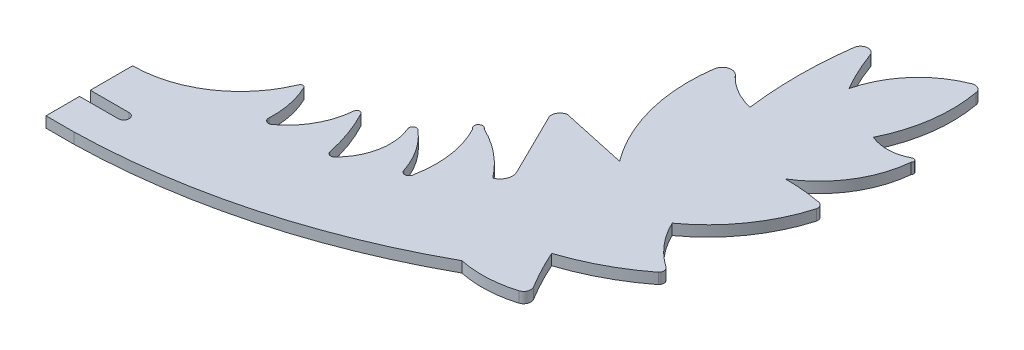
SolidWorks part; units mm, degrees
ref_plane "Front Plane" through (0, 0, 0) normal (0, 0, 1) x (1, 0, 0)
ref_plane "Top Plane" through (0, 0, 0) normal (0, 1, 0) x (1, 0, 0)
ref_plane "Right Plane" through (0, 0, 0) normal (1, 0, 0) x (0, 0, -1)
sketch "Sketch1" plane through (0, 0, 0) normal (0, 1, 0) x (1, 0, 0)
  line L0 (-27.5665, 0) -> (0, 0)
  line L1 (51.6934, 52.0615) -> (42.7702, 70.1336)
  line L2 (44.8222, 73.0639) -> (63.4273, 69.0275)
  line L5 (0, -55) -> (0, 55) construction
  line L6 (-27.5665, 12.36) -> (-27.5665, 24.16)
  line L7 (-16.7465, 12.36) -> (-27.5665, 12.36)
  line L8 (-27.5665, 9.36) -> (-16.7465, 9.36)
  line L9 (-27.5665, 0) -> (-27.5665, 9.36)
  arc A0 (65.4335, 23) -> (-27.5665, 0) centre (-23.695, 183.8672) cw
  arc A1 (-27.5665, 24.16) -> (0.1965, 42.7514) centre (-27.5665, 54.1853) ccw
  arc A2 (0.1965, 42.7514) -> (1.5651, 42.7913) centre (0.8897, 42.4659) cw
  arc A3 (1.5651, 42.7913) -> (4.0418, 30.5532) centre (-21.2317, 31.8081) cw
  arc A4 (4.0418, 30.5532) -> (6.1177, 29.4432) centre (5.342, 30.4886) ccw
  arc A5 (6.1177, 29.4432) -> (14.2192, 44.1293) centre (-5.9138, 45.658) ccw
  arc A6 (14.2192, 44.1293) -> (15.8307, 44.4694) centre (15.0746, 44.0643) cw
  arc A7 (-16.7465, 9.36) -> (-16.7465, 12.36) centre (-16.7465, 10.86) ccw
  arc A8 (15.8307, 44.4694) -> (20.701, 30.9459) centre (-27.6807, 21.1607) cw
  arc A9 (20.701, 30.9459) -> (22.6994, 30.3411) centre (21.8628, 31.1809) ccw
  arc A10 (22.6994, 30.3411) -> (26.0288, 47.3299) centre (11.7813, 41.3015) ccw
  arc A11 (26.0288, 47.3299) -> (27.6551, 48.5262) centre (26.9845, 47.7343) cw
  arc A12 (27.6551, 48.5262) -> (35.4716, 36.8845) centre (11.0793, 28.9519) cw
  arc A13 (35.4716, 36.8845) -> (37.9633, 37.283) centre (36.7167, 37.088) ccw
  arc A14 (37.9633, 37.283) -> (35.1798, 56.295) centre (9.5526, 42.8333) ccw
  arc A15 (35.1798, 56.295) -> (36.7167, 57.9401) centre (35.7014, 57.3482) cw
  arc A16 (36.7167, 57.9401) -> (49.793, 47.2722) centre (21.0347, 25.3696) cw
  arc A17 (49.793, 47.2722) -> (51.6934, 52.0615) centre (48.5811, 50.5248) ccw
  arc A18 (42.7702, 70.1336) -> (44.8222, 73.0639) centre (45.2614, 70.5727) cw
  arc A19 (63.4273, 69.0275) -> (54.3156, 104.5801) centre (101.9153, 97.8355) cw
  arc A20 (54.3156, 104.5801) -> (59.0261, 105.6552) centre (56.8764, 104.2172) cw
  arc A21 (59.0261, 105.6552) -> (68.5773, 100.2596) centre (72.8313, 118.9413) ccw
  arc A22 (68.5773, 100.2596) -> (68.6398, 129.2319) centre (177.7359, 114.5101) cw
  arc A23 (68.6398, 129.2319) -> (72.5962, 129.8796) centre (70.7169, 128.9517) cw
  arc A24 (72.5962, 129.8796) -> (77.8585, 118.5351) centre (141.6753, 155.0296) ccw
  arc A25 (77.8585, 118.5351) -> (93.8783, 136.8933) centre (103.4218, 112.3966) cw
  arc A26 (93.8783, 136.8933) -> (96.5302, 135.4171) centre (94.5934, 135.0578) cw
  arc A27 (96.5302, 135.4171) -> (93.0404, 110.2242) centre (56.9097, 128.0674) cw
  arc A28 (93.0404, 110.2242) -> (103.4392, 110.6194) centre (97.8322, 121.1468) ccw
  arc A29 (103.4392, 110.6194) -> (104.3131, 109.4209) centre (103.7913, 109.9583) cw
  arc A30 (104.3131, 109.4209) -> (90.8087, 87.8697) centre (76.0244, 112.1405) cw
  arc A31 (90.8087, 87.8697) -> (101.0475, 86.9282) centre (91.1003, 34.8981) cw
  arc A32 (101.0475, 86.9282) -> (102.3573, 84.972) centre (100.7369, 85.3036) cw
  arc A33 (102.3573, 84.972) -> (85.7098, 61.4012) centre (59.7142, 97.4256) cw
  arc A34 (85.7098, 61.4012) -> (95.666, 49.7824) centre (112.4138, 74.2089) ccw
  arc A35 (95.666, 49.7824) -> (95.6686, 47.6295) centre (94.5934, 48.7047) cw
  arc A36 (95.6686, 47.6295) -> (76.2021, 37.2862) centre (56.0536, 98.6963) cw
  arc A37 (76.2021, 37.2862) -> (81.7847, 26.6623) centre (162.3655, 75.7842) ccw
  arc A38 (81.7847, 26.6623) -> (80.6469, 23.6832) centre (80.0633, 25.613) cw
  arc A39 (80.6469, 23.6832) -> (65.4335, 23) centre (71.6955, 53.2842) cw
  point P0 (-15.2465, 10.86)
  point P6 (65.4335, 23)
  point P30 (0, 0)
  point P40 (95.4335, 136.39)
  point P51 (104.0535, 110.66)
  dimension "D3" = 1.5
  dimension "D11" = 183.9079
  dimension "D12" = 30.0253
  dimension "D13" = 0.7497
  dimension "D14" = 25.3046
  dimension "D15" = 1.3018
  dimension "D16" = 20.191
  dimension "D17" = 0.8578
  dimension "D18" = 49.3613
  dimension "D19" = 1.1853
  dimension "D20" = 15.4704
  dimension "D21" = 1.0377
  dimension "D22" = 25.6497
  dimension "D23" = 1.2617
  dimension "D24" = 28.9477
  dimension "D25" = 1.1753
  dimension "D26" = 36.1492
  dimension "D27" = 3.471
  dimension "D28" = 2.5296
  dimension "D29" = 48.0751
  dimension "D30" = 2.5863
  dimension "D31" = 19.1599
  dimension "D32" = 110.0849
  dimension "D33" = 2.0959
  dimension "D34" = 73.5149
  dimension "D35" = 26.29
  dimension "D36" = 1.9698
  dimension "D37" = 40.2965
  dimension "D38" = 11.9274
  dimension "D39" = 0.749
  dimension "D40" = 28.4191
  dimension "D41" = 52.9724
  dimension "D42" = 1.654
  dimension "D43" = 44.4244
  dimension "D44" = 29.6165
  dimension "D45" = 1.5205
  dimension "D46" = 64.6309
  dimension "D47" = 94.3728
  dimension "D48" = 2.016
  dimension "D49" = 30.9249
  dimension "D1" = 9.36
  dimension "D2" = 11.8
  dimension "D4" = 12.32
  dimension "D5" = 23
  dimension "D6" = 93
  dimension "D7" = 131.62
  dimension "D8" = 110.66
  dimension "D9" = 136.39
  dimension "D10" = 123
  dimension "D50" = 0.1965
  dimension "D51" = 0.8897
  dimension "D52" = 1.5651
  dimension "D53" = 4.0418
  dimension "D54" = 6.1177
  dimension "D55" = 11.0793
  dimension "D56" = 9.5526
  dimension "D57" = 11.7813
  dimension "D58" = 14.2192
  dimension "D59" = 15.8307
  dimension "D60" = 20.701
  dimension "D61" = 26.0288
  dimension "D62" = 54.3156
  dimension "D63" = 21.0347
  dimension "D64" = 56.0536
  dimension "D65" = 56.8764
  dimension "D66" = 56.9097
  dimension "D67" = 59.7142
  dimension "D68" = 68.6398
  dimension "D69" = 35.1798
  dimension "D70" = 35.4716
  dimension "D71" = 35.7014
  dimension "D72" = 36.7167
  dimension "D73" = 37.9633
  dimension "D74" = 42.7702
  dimension "D75" = 44.8222
  dimension "D76" = 45.2614
  dimension "D77" = 48.5811
  dimension "D78" = 49.793
  dimension "D79" = 51.6934
  dimension "D80" = 70.7169
  dimension "D81" = 71.6955
  dimension "D82" = 76.0244
  dimension "D83" = 76.2021
  dimension "D84" = 59.0261
  dimension "D85" = 80.0633
  dimension "D86" = 63.4273
  dimension "D87" = 81.7847
  dimension "D88" = 68.5773
  dimension "D89" = 85.7098
  dimension "D90" = 90.8087
  dimension "D91" = 91.1003
  dimension "D92" = 72.5962
  dimension "D93" = 72.8313
  dimension "D94" = 93.8783
  dimension "D95" = 94.5934
  dimension "D96" = 77.8585
  dimension "D97" = 95.666
  dimension "D98" = 95.6686
  dimension "D99" = 97.8322
  dimension "D100" = 100.7369
  dimension "D101" = 102.3573
  dimension "D102" = 103.4392
  dimension "D103" = 93.0404
  dimension "D104" = 104.3131
  dimension "D119" = 141.6753
extrude "Boss-Extrude1" add sketch "Sketch1" along normal blind 3 contours A39 A38 A37 A36 A35 A34 A33 A32 A31 A30 A29 A28 A27 A26 A25 A24 A23 A22 A21 A20 A19 L2 A18 L1 A17 A16 A15 A14 A13 A12 A11 A10 A9 A8 A6 A5 A4 A3 A2 A1 L6 L7 A7 L8 L9 L0 A0
